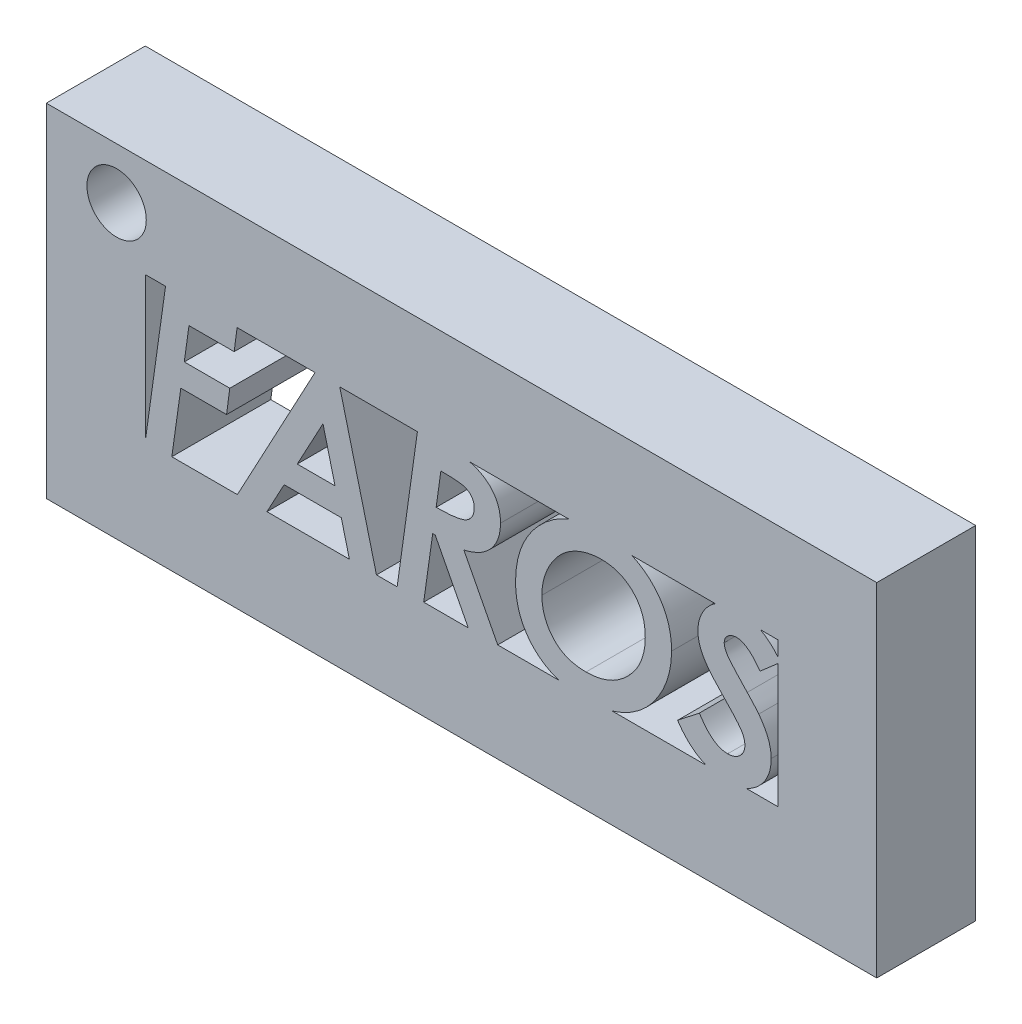
SolidWorks part; units mm, degrees
ref_plane "Front Plane" through (0, 0, 0) normal (0, 0, 1) x (1, 0, 0)
ref_plane "Top Plane" through (0, 0, 0) normal (0, 1, 0) x (1, 0, 0)
ref_plane "Right Plane" through (0, 0, 0) normal (1, 0, 0) x (0, 0, -1)
sketch "Sketch9" plane through (0, 0, 0) normal (0, 0, 1) x (1, 0, 0)
  line L0 (0, 0) -> (-25, 0) construction
  text T0 "FAROS" font "Century Gothic" height in points 28
  dimension "D1" = 25
extrude "Boss-Extrude4" add sketch "Sketch9" along normal blind 5
sketch "Sketch11" plane through (0, 0, 5) normal (0, 0, 1) x (1, 0, 0)
  line L0 (-26.9081, -4.6227) -> (-26.9081, 12.6801)
  line L1 (-21.9081, 0.3773) -> (10.0531, 0.3773)
  line L2 (-21.9081, 0.3773) -> (-21.9081, 7.6801)
  line L3 (-21.9081, 7.6801) -> (10.0531, 7.6801)
  line L4 (10.0531, 0.3773) -> (10.0531, 7.6801)
  line L5 (-26.9081, 12.6801) -> (15.0531, 12.6801)
  line L6 (15.0531, -4.6227) -> (15.0531, 12.6801)
  line L7 (-26.9081, -4.6227) -> (15.0531, -4.6227)
  circle A0 centre (-23.3564, 10.0915) radius 1.5
  point P11 (-23.3564, 10.0915)
  dimension "D2" = 3
  dimension "D1" = 5
extrude "Boss-Extrude6" add sketch "Sketch11" against normal blind 5
